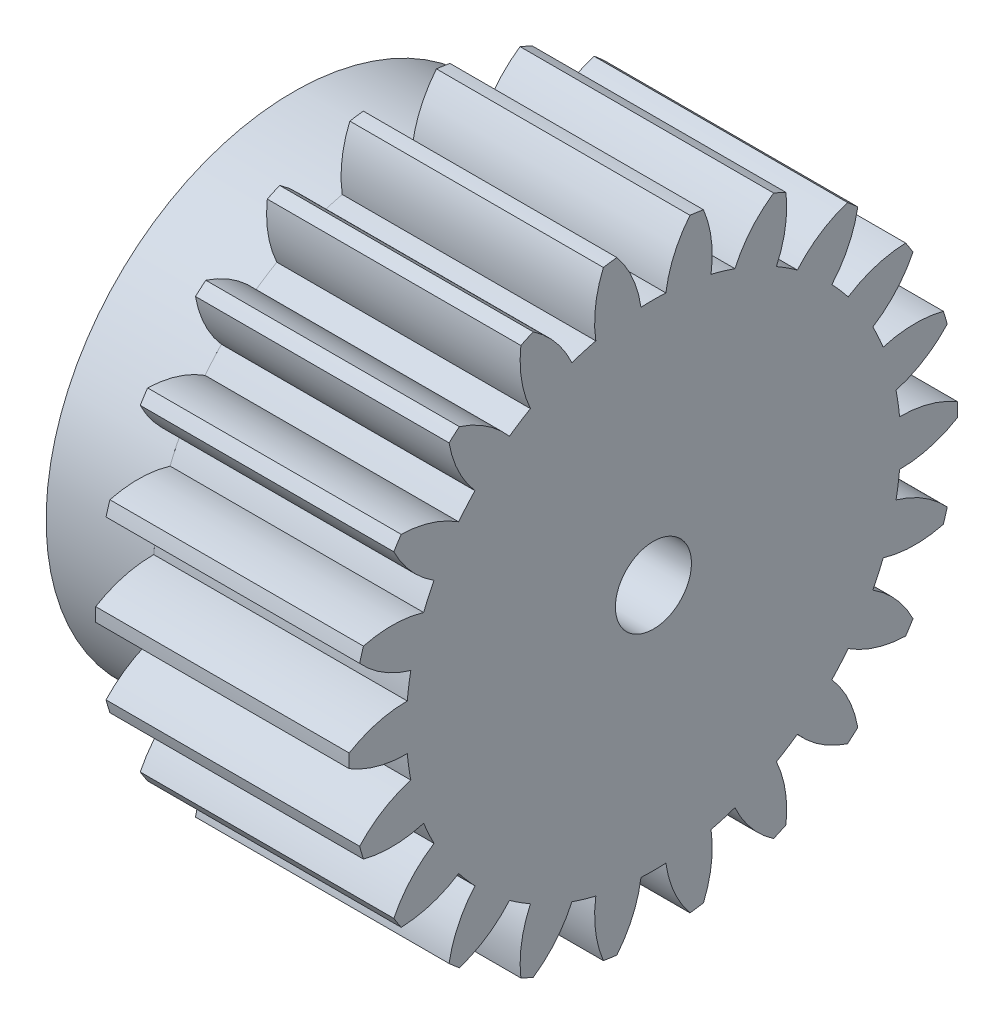
SolidWorks part; units mm, degrees
ref_plane "Front Plane" through (0, 0, 0) normal (0, 0, 1) x (1, 0, 0)
ref_plane "Top Plane" through (0, 0, 0) normal (0, 1, 0) x (1, 0, 0)
ref_plane "Right Plane" through (0, 0, 0) normal (1, 0, 0) x (0, 0, -1)
ref_plane "Plane2" through (4.0389, 0, 0) normal (1, 0, 0) x (0, 0, -1)
sketch "Sketch8" plane through (4.0389, 0, 0) normal (1, 0, 0) x (0, 0, -1)
  circle A0 centre (3.23, 4.4522) radius 1.5
  arc A1 (-8.767, 4.1839) -> (-6.4774, 3.5525) centre (-6.496, 7.9525) ccw
  arc A2 (-6.4774, 3.5525) -> (-6.3377, 2.5805) centre (3.23, 4.4522) ccw
  arc A3 (-6.3377, 2.5805) -> (-8.3567, 1.3296) centre (-5.1159, -1.6464) ccw
  arc A4 (-8.3567, 1.3296) -> (-8.2055, 0.8148) centre (3.23, 4.4522) ccw
  arc A5 (-8.2055, 0.8148) -> (-5.8308, 0.8541) centre (-7.0882, 5.0706) ccw
  arc A6 (-5.8308, 0.8541) -> (-5.4228, -0.0392) centre (3.23, 4.4522) ccw
  arc A7 (-5.4228, -0.0392) -> (-7.0076, -1.8082) centre (-3.0596, -3.7507) ccw
  arc A8 (-7.0076, -1.8082) -> (-6.7175, -2.2596) centre (3.23, 4.4522) ccw
  arc A9 (-6.7175, -2.2596) -> (-4.45, -1.5529) centre (-6.8444, 2.1386) ccw
  arc A10 (-4.45, -1.5529) -> (-3.807, -2.295) centre (3.23, 4.4522) ccw
  arc A11 (-3.807, -2.295) -> (-4.8292, -4.4389) centre (-0.4938, -5.1904) ccw
  arc A12 (-4.8292, -4.4389) -> (-4.4237, -4.7902) centre (3.23, 4.4522) ccw
  arc A13 (-4.4237, -4.7902) -> (-2.4471, -3.4733) centre (-5.7845, -0.606) ccw
  arc A14 (-2.4471, -3.4733) -> (-1.621, -4.0043) centre (3.23, 4.4522) ccw
  arc A15 (-1.621, -4.0043) -> (-1.9978, -6.3492) centre (2.3736, -5.8489) ccw
  arc A16 (-1.9978, -6.3492) -> (-1.5097, -6.5721) centre (3.23, 4.4522) ccw
  arc A17 (-1.5097, -6.5721) -> (0.0157, -4.7517) centre (-3.9943, -2.9408) ccw
  arc A18 (0.0157, -4.7517) -> (0.9579, -5.0284) centre (3.23, 4.4522) ccw
  arc A19 (0.9579, -5.0284) -> (1.257, -7.3845) centre (5.3105, -5.6729) ccw
  arc A20 (1.257, -7.3845) -> (1.7882, -7.4609) centre (3.23, 4.4522) ccw
  arc A21 (1.7882, -7.4609) -> (2.739, -5.2845) centre (-1.6189, -4.6766) ccw
  arc A22 (2.739, -5.2845) -> (3.721, -5.2845) centre (3.23, 4.4522) ccw
  arc A23 (3.721, -5.2845) -> (4.6718, -7.4609) centre (8.0788, -4.6766) ccw
  arc A24 (4.6718, -7.4609) -> (5.2029, -7.3845) centre (3.23, 4.4522) ccw
  arc A25 (5.2029, -7.3845) -> (5.502, -5.0284) centre (1.1494, -5.6729) ccw
  arc A26 (5.502, -5.0284) -> (6.4442, -4.7517) centre (3.23, 4.4522) ccw
  arc A27 (6.4442, -4.7517) -> (7.9696, -6.5721) centre (10.4542, -2.9408) ccw
  arc A28 (7.9696, -6.5721) -> (8.4577, -6.3492) centre (3.23, 4.4522) ccw
  arc A29 (8.4577, -6.3492) -> (8.0809, -4.0043) centre (4.0863, -5.8489) ccw
  arc A30 (8.0809, -4.0043) -> (8.907, -3.4733) centre (3.23, 4.4522) ccw
  arc A31 (8.907, -3.4733) -> (10.8836, -4.7902) centre (12.2444, -0.606) ccw
  arc A32 (10.8836, -4.7902) -> (11.2891, -4.4389) centre (3.23, 4.4522) ccw
  arc A33 (11.2891, -4.4389) -> (10.2669, -2.295) centre (6.9537, -5.1904) ccw
  arc A34 (10.2669, -2.295) -> (10.9099, -1.5529) centre (3.23, 4.4522) ccw
  arc A35 (10.9099, -1.5529) -> (13.1774, -2.2596) centre (13.3043, 2.1386) ccw
  arc A36 (13.1774, -2.2596) -> (13.4675, -1.8082) centre (3.23, 4.4522) ccw
  arc A37 (13.4675, -1.8082) -> (11.8827, -0.0392) centre (9.5195, -3.7507) ccw
  arc A38 (11.8827, -0.0392) -> (12.2907, 0.8541) centre (3.23, 4.4522) ccw
  arc A39 (12.2907, 0.8541) -> (14.6654, 0.8148) centre (13.5481, 5.0706) ccw
  arc A40 (14.6654, 0.8148) -> (14.8166, 1.3296) centre (3.23, 4.4522) ccw
  arc A41 (14.8166, 1.3296) -> (12.7976, 2.5805) centre (11.5758, -1.6464) ccw
  arc A42 (12.7976, 2.5805) -> (12.9374, 3.5525) centre (3.23, 4.4522) ccw
  arc A43 (12.9374, 3.5525) -> (15.227, 4.1839) centre (12.9559, 7.9525) ccw
  arc A44 (15.227, 4.1839) -> (15.227, 4.7205) centre (3.23, 4.4522) ccw
  arc A45 (15.227, 4.7205) -> (12.9374, 5.3518) centre (12.9559, 0.9519) ccw
  arc A46 (12.9374, 5.3518) -> (12.7976, 6.3238) centre (3.23, 4.4522) ccw
  arc A47 (12.7976, 6.3238) -> (14.8166, 7.5747) centre (11.5758, 10.5508) ccw
  arc A48 (14.8166, 7.5747) -> (14.6654, 8.0895) centre (3.23, 4.4522) ccw
  arc A49 (14.6654, 8.0895) -> (12.2907, 8.0503) centre (13.5481, 3.8338) ccw
  arc A50 (12.2907, 8.0503) -> (11.8827, 8.9435) centre (3.23, 4.4522) ccw
  arc A51 (11.8827, 8.9435) -> (13.4675, 10.7125) centre (9.5195, 12.655) ccw
  arc A52 (13.4675, 10.7125) -> (13.1774, 11.1639) centre (3.23, 4.4522) ccw
  arc A53 (13.1774, 11.1639) -> (10.9099, 10.4572) centre (13.3043, 6.7658) ccw
  arc A54 (10.9099, 10.4572) -> (10.2669, 11.1994) centre (3.23, 4.4522) ccw
  arc A55 (10.2669, 11.1994) -> (11.2891, 13.3432) centre (6.9537, 14.0947) ccw
  arc A56 (11.2891, 13.3432) -> (10.8836, 13.6946) centre (3.23, 4.4522) ccw
  arc A57 (10.8836, 13.6946) -> (8.907, 12.3777) centre (12.2444, 9.5103) ccw
  arc A58 (8.907, 12.3777) -> (8.0809, 12.9086) centre (3.23, 4.4522) ccw
  arc A59 (8.0809, 12.9086) -> (8.4577, 15.2536) centre (4.0863, 14.7533) ccw
  arc A60 (8.4577, 15.2536) -> (7.9696, 15.4765) centre (3.23, 4.4522) ccw
  arc A61 (7.9696, 15.4765) -> (6.4442, 13.6561) centre (10.4542, 11.8451) ccw
  arc A62 (6.4442, 13.6561) -> (5.502, 13.9327) centre (3.23, 4.4522) ccw
  arc A63 (5.502, 13.9327) -> (5.2029, 16.2889) centre (1.1494, 14.5772) ccw
  arc A64 (5.2029, 16.2889) -> (4.6718, 16.3652) centre (3.23, 4.4522) ccw
  arc A65 (4.6718, 16.3652) -> (3.721, 14.1888) centre (8.0788, 13.581) ccw
  arc A66 (3.721, 14.1888) -> (2.739, 14.1888) centre (3.23, 4.4522) ccw
  arc A67 (2.739, 14.1888) -> (1.7882, 16.3652) centre (-1.6189, 13.581) ccw
  arc A68 (1.7882, 16.3652) -> (1.257, 16.2889) centre (3.23, 4.4522) ccw
  arc A69 (1.257, 16.2889) -> (0.9579, 13.9327) centre (5.3105, 14.5772) ccw
  arc A70 (0.9579, 13.9327) -> (0.0157, 13.6561) centre (3.23, 4.4522) ccw
  arc A71 (0.0157, 13.6561) -> (-1.5097, 15.4765) centre (-3.9943, 11.8451) ccw
  arc A72 (-1.5097, 15.4765) -> (-1.9978, 15.2536) centre (3.23, 4.4522) ccw
  arc A73 (-1.9978, 15.2536) -> (-1.621, 12.9086) centre (2.3736, 14.7533) ccw
  arc A74 (-1.621, 12.9086) -> (-2.4471, 12.3777) centre (3.23, 4.4522) ccw
  arc A75 (-2.4471, 12.3777) -> (-4.4237, 13.6946) centre (-5.7845, 9.5103) ccw
  arc A76 (-4.4237, 13.6946) -> (-4.8292, 13.3432) centre (3.23, 4.4522) ccw
  arc A77 (-4.8292, 13.3432) -> (-3.807, 11.1994) centre (-0.4938, 14.0947) ccw
  arc A78 (-3.807, 11.1994) -> (-4.45, 10.4572) centre (3.23, 4.4522) ccw
  arc A79 (-4.45, 10.4572) -> (-6.7175, 11.1639) centre (-6.8444, 6.7658) ccw
  arc A80 (-6.7175, 11.1639) -> (-7.0076, 10.7125) centre (3.23, 4.4522) ccw
  arc A81 (-7.0076, 10.7125) -> (-5.4228, 8.9435) centre (-3.0596, 12.655) ccw
  arc A82 (-5.4228, 8.9435) -> (-5.8308, 8.0503) centre (3.23, 4.4522) ccw
  arc A83 (-5.8308, 8.0503) -> (-8.2055, 8.0895) centre (-7.0882, 3.8338) ccw
  arc A84 (-8.2055, 8.0895) -> (-8.3567, 7.5747) centre (3.23, 4.4522) ccw
  arc A85 (-8.3567, 7.5747) -> (-6.3377, 6.3238) centre (-5.1159, 10.5508) ccw
  arc A86 (-6.3377, 6.3238) -> (-6.4774, 5.3518) centre (3.23, 4.4522) ccw
  arc A87 (-6.4774, 5.3518) -> (-8.767, 4.7205) centre (-6.496, 0.9519) ccw
  arc A88 (-8.767, 4.7205) -> (-8.767, 4.1839) centre (3.23, 4.4522) ccw
extrude "Boss-Extrude1" add sketch "Sketch8" against normal blind 10 separate body
ref_plane "Plane3" through (0, 0, -3.23) normal (0, 0, 1) x (1, 0, 0)
sketch "Sketch13" plane through (0, 0, -3.23) normal (0, 0, 1) x (1, 0, 0)
  line L0 (-10.1611, 14.2022) -> (-10.1611, 4.4522)
  line L1 (-10.1611, 4.4522) -> (-5.9611, 4.4522)
  line L2 (-5.9611, 4.4522) -> (-5.9611, 14.2022)
  line L3 (-5.9611, 14.2022) -> (-10.1611, 14.2022)
  line L4 (-10.1611, 4.4522) -> (-5.9611, 4.4522) construction
revolve "Revolve2" add sketch "Sketch13" angle 360 about L1
ref_plane "Plane4" through (-10.1611, 0, 0) normal (-1, 0, 0) x (0, 0, 1)
sketch "Sketch19" plane through (-10.1611, 0, 0) normal (-1, 0, 0) x (0, 0, 1)
  line L0 (-6.0636, 5.0688) -> (-5.9087, 4.7906)
  line L1 (-5.9087, 4.7906) -> (-6.128, 4.5596)
  line L2 (-6.128, 4.3448) -> (-5.9087, 4.1138)
  line L3 (-5.9087, 4.1138) -> (-6.0636, 3.8355)
  line L4 (-6.0102, 3.6274) -> (-5.7404, 3.4582)
  line L5 (-5.7404, 3.4582) -> (-5.8212, 3.1502)
  line L6 (-5.7177, 2.9619) -> (-5.4143, 2.8652)
  line L7 (-5.4143, 2.8652) -> (-5.416, 2.5467)
  line L8 (-5.269, 2.39) -> (-4.951, 2.3718)
  line L9 (-4.951, 2.3718) -> (-4.8735, 2.0629)
  line L10 (-4.6921, 1.9477) -> (-4.3796, 2.0091)
  line L11 (-4.3796, 2.0091) -> (-4.2277, 1.7292)
  line L12 (-4.0233, 1.6628) -> (-3.7359, 1.8)
  line L13 (-3.7359, 1.8) -> (-3.5191, 1.5666)
  line L14 (-3.3047, 1.5531) -> (-3.0604, 1.7575)
  line L15 (-3.0604, 1.7575) -> (-2.7924, 1.5854)
  line L16 (-2.5814, 1.6256) -> (-2.3956, 1.8843)
  line L17 (-2.3956, 1.8843) -> (-2.0932, 1.7842)
  line L18 (-1.8988, 1.8757) -> (-1.7832, 2.1725)
  line L19 (-1.7832, 2.1725) -> (-1.4655, 2.1507)
  line L20 (-1.2999, 2.2877) -> (-1.2617, 2.6039)
  line L21 (-1.2617, 2.6039) -> (-0.9486, 2.6619)
  line L22 (-0.8223, 2.8357) -> (-0.8639, 3.1514)
  line L23 (-0.8639, 3.1514) -> (-0.575, 3.2855)
  line L24 (-0.4959, 3.4852) -> (-0.6148, 3.7807)
  line L25 (-0.6148, 3.7807) -> (-0.3683, 3.9824)
  line L26 (-0.3413, 4.1955) -> (-0.53, 4.4522)
  line L27 (-0.53, 4.4522) -> (-0.3413, 4.7088)
  line L28 (-0.3683, 4.922) -> (-0.6148, 5.1236)
  line L29 (-0.6148, 5.1236) -> (-0.4959, 5.4191)
  line L30 (-0.575, 5.6189) -> (-0.8639, 5.7529)
  line L31 (-0.8639, 5.7529) -> (-0.8223, 6.0687)
  line L32 (-0.9486, 6.2425) -> (-1.2617, 6.3005)
  line L33 (-1.2617, 6.3005) -> (-1.2999, 6.6167)
  line L34 (-1.4655, 6.7536) -> (-1.7832, 6.7319)
  line L35 (-1.7832, 6.7319) -> (-1.8988, 7.0286)
  line L36 (-2.0932, 7.1201) -> (-2.3956, 7.02)
  line L37 (-2.3956, 7.02) -> (-2.5814, 7.2787)
  line L38 (-2.7924, 7.319) -> (-3.0604, 7.1468)
  line L39 (-3.0604, 7.1468) -> (-3.3047, 7.3512)
  line L40 (-3.5191, 7.3377) -> (-3.7359, 7.1043)
  line L41 (-3.7359, 7.1043) -> (-4.0233, 7.2415)
  line L42 (-4.2277, 7.1752) -> (-4.3796, 6.8952)
  line L43 (-4.3796, 6.8952) -> (-4.6921, 6.9566)
  line L44 (-4.8735, 6.8415) -> (-4.951, 6.5326)
  line L45 (-4.951, 6.5326) -> (-5.269, 6.5143)
  line L46 (-5.416, 6.3577) -> (-5.4143, 6.0392)
  line L47 (-5.4143, 6.0392) -> (-5.7177, 5.9424)
  line L48 (-5.8212, 5.7542) -> (-5.7404, 5.4461)
  line L49 (-5.7404, 5.4461) -> (-6.0102, 5.2769)
  arc A0 (-6.0102, 5.2769) -> (-6.0636, 5.0688) centre (-3.23, 4.4522) ccw
  arc A1 (-6.128, 4.5596) -> (-6.128, 4.3448) centre (-3.23, 4.4522) ccw
  arc A2 (-6.0636, 3.8355) -> (-6.0102, 3.6274) centre (-3.23, 4.4522) ccw
  arc A3 (-5.8212, 3.1502) -> (-5.7177, 2.9619) centre (-3.23, 4.4522) ccw
  arc A4 (-5.416, 2.5467) -> (-5.269, 2.39) centre (-3.23, 4.4522) ccw
  arc A5 (-4.8735, 2.0629) -> (-4.6921, 1.9477) centre (-3.23, 4.4522) ccw
  arc A6 (-4.2277, 1.7292) -> (-4.0233, 1.6628) centre (-3.23, 4.4522) ccw
  arc A7 (-3.5191, 1.5666) -> (-3.3047, 1.5531) centre (-3.23, 4.4522) ccw
  arc A8 (-2.7924, 1.5854) -> (-2.5814, 1.6256) centre (-3.23, 4.4522) ccw
  arc A9 (-2.0932, 1.7842) -> (-1.8988, 1.8757) centre (-3.23, 4.4522) ccw
  arc A10 (-1.4655, 2.1507) -> (-1.2999, 2.2877) centre (-3.23, 4.4522) ccw
  arc A11 (-0.9486, 2.6619) -> (-0.8223, 2.8357) centre (-3.23, 4.4522) ccw
  arc A12 (-0.575, 3.2855) -> (-0.4959, 3.4852) centre (-3.23, 4.4522) ccw
  arc A13 (-0.3683, 3.9824) -> (-0.3413, 4.1955) centre (-3.23, 4.4522) ccw
  arc A14 (-0.3413, 4.7088) -> (-0.3683, 4.922) centre (-3.23, 4.4522) ccw
  arc A15 (-0.4959, 5.4191) -> (-0.575, 5.6189) centre (-3.23, 4.4522) ccw
  arc A16 (-0.8223, 6.0687) -> (-0.9486, 6.2425) centre (-3.23, 4.4522) ccw
  arc A17 (-1.2999, 6.6167) -> (-1.4655, 6.7536) centre (-3.23, 4.4522) ccw
  arc A18 (-1.8988, 7.0286) -> (-2.0932, 7.1201) centre (-3.23, 4.4522) ccw
  arc A19 (-2.5814, 7.2787) -> (-2.7924, 7.319) centre (-3.23, 4.4522) ccw
  arc A20 (-3.3047, 7.3512) -> (-3.5191, 7.3377) centre (-3.23, 4.4522) ccw
  arc A21 (-4.0233, 7.2415) -> (-4.2277, 7.1752) centre (-3.23, 4.4522) ccw
  arc A22 (-4.6921, 6.9566) -> (-4.8735, 6.8415) centre (-3.23, 4.4522) ccw
  arc A23 (-5.269, 6.5143) -> (-5.416, 6.3577) centre (-3.23, 4.4522) ccw
  arc A24 (-5.7177, 5.9424) -> (-5.8212, 5.7542) centre (-3.23, 4.4522) ccw
extrude "Cut-Extrude2" cut sketch "Sketch19" against normal blind 3.2
hole_wizard "Ø3.0 (3) Diameter Hole2" positions "Sketch21" profile "Sketch20" hole size "Ø3.0" standard "ANSI Metric"
sketch "Sketch21" plane through (-5.9611, 0, 0) normal (1, 0, 0) x (0, 0, -1)
  point P0 (3.23, 4.4522)
sketch "Sketch20" plane through (-5.9611, 4.4522, -3.23) normal (0, 1, 0) x (0, 0, -1)
  line L0 (0, 0) -> (0, 4.2)
  line L1 (0, 4.2) -> (1.5, 4.2)
  line L2 (1.5, 4.2) -> (1.5, 0)
  line L5 (1.5, 0) -> (0, 0)
  line L11 (0, -6.35) -> (0, 107.95) construction
  dimension "Thru Hole Dia." = 3
  dimension "Thru Hole Depth" = 4.2
